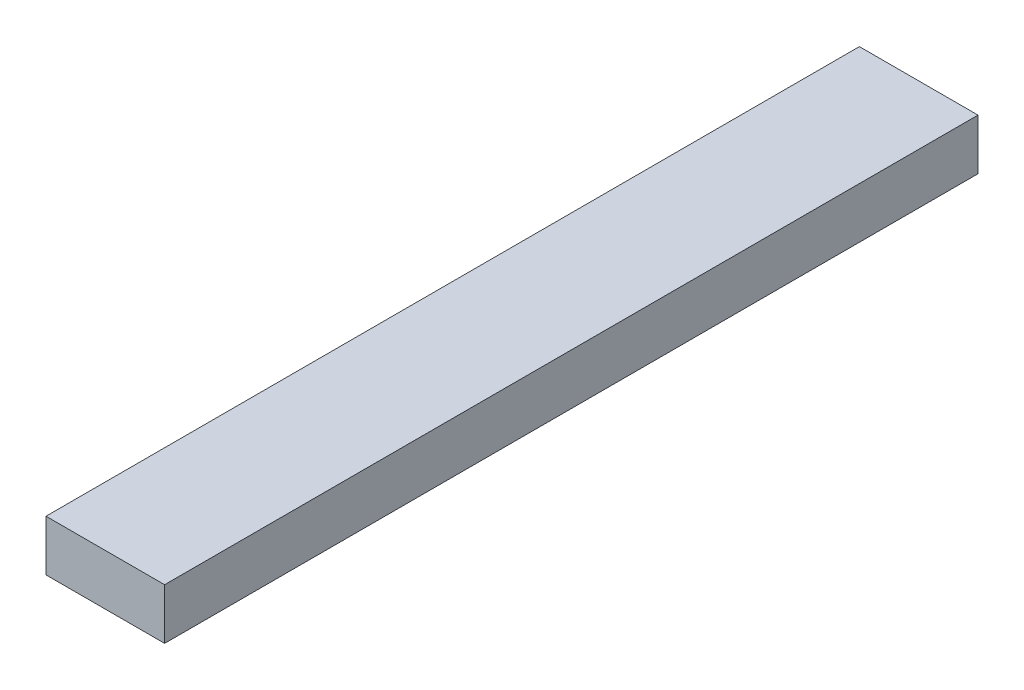
SolidWorks part; units mm, degrees
ref_plane "Front Plane" through (0, 0, 0) normal (0, 0, 1) x (1, 0, 0)
ref_plane "Top Plane" through (0, 0, 0) normal (0, 1, 0) x (1, 0, 0)
ref_plane "Right Plane" through (0, 0, 0) normal (1, 0, 0) x (0, 0, -1)
sketch "Sketch1" plane through (0, 0, 0) normal (0, 0, 1) x (1, 0, 0)
  line L1 (-44.45, -19.05) -> (44.45, -19.05)
  line L2 (-44.45, -19.05) -> (-44.45, 19.05)
  line L3 (-44.45, 19.05) -> (44.45, 19.05)
  line L4 (44.45, -19.05) -> (44.45, 19.05)
  line L5 (-44.45, -19.05) -> (44.45, 19.05) construction
  line L6 (-44.45, 19.05) -> (44.45, -19.05) construction
  point P0 (0, 0)
  dimension "D1" = 38.1
  dimension "D2" = 88.9
extrude "Boss-Extrude1" add sketch "Sketch1" along normal mid plane 609.6
